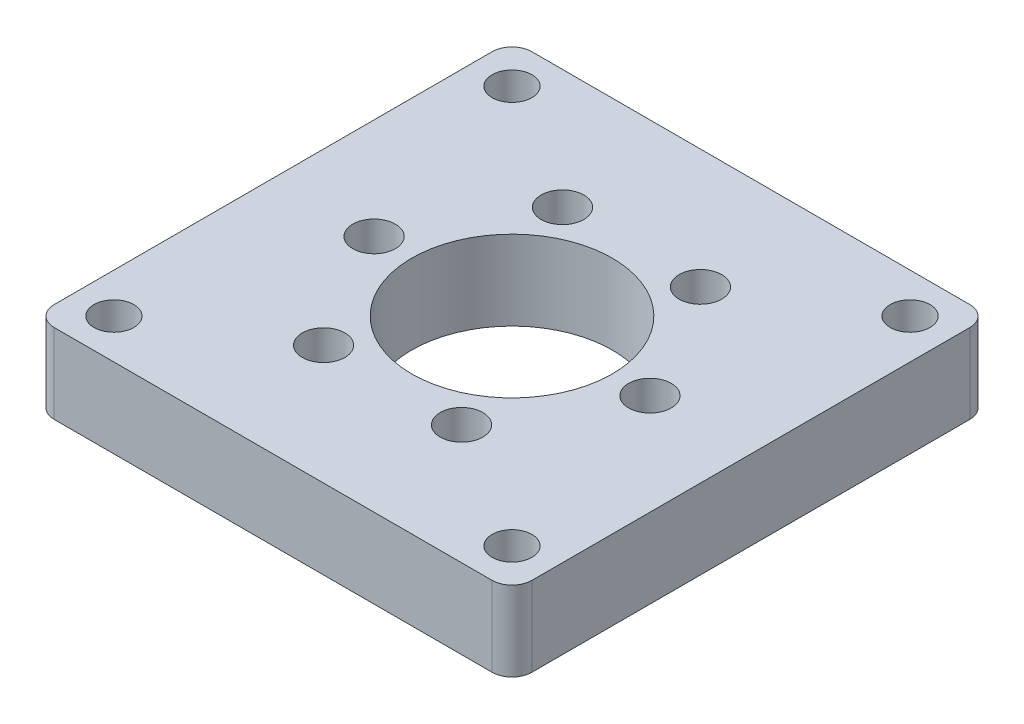
SolidWorks part; units mm, degrees
material "Balsa"
ref_plane "Front Plane" through (0, 0, 0) normal (0, 0, 1) x (1, 0, 0)
ref_plane "Top Plane" through (0, 0, 0) normal (0, 1, 0) x (1, 0, 0)
ref_plane "Right Plane" through (0, 0, 0) normal (1, 0, 0) x (0, 0, -1)
sketch "Sketch1" plane through (0, 0, 0) normal (0, 1, 0) x (1, 0, 0)
  line L1 (0, 0) -> (-38.1, 0)
  line L2 (0, 0) -> (0, -38.1)
  line L3 (0, -38.1) -> (-38.1, -38.1)
  line L4 (-38.1, 0) -> (-38.1, -38.1)
  dimension "D1" = 38.1
  dimension "D2" = 38.1
extrude "Boss-Extrude1" add sketch "Sketch1" along normal blind 6.35
sketch "Sketch5" plane through (0, 6.35, 0) normal (0, 1, 0) x (1, 0, 0)
  line L0 (-38.1, -19.05) -> (0, -19.05) construction
  line L1 (-38.1, 0) -> (-38.1, -38.1) construction
  line L2 (0, -38.1) -> (0, 0) construction
  circle A0 centre (-19.05, -19.05) radius 8
  dimension "D1" = 16
extrude "Cut-Extrude1" cut sketch "Sketch5" against normal through all
hole_wizard "M3 Clearance Hole1" positions "Sketch4" profile "Sketch3" hole size "M3" standard "Ansi Metric" end condition through all
sketch "Sketch4" plane through (0, 6.35, 0) normal (0, 1, 0) x (-1, 0, 0)
  line L0 (38.1, 19.05) -> (0, 19.05) construction
  line L1 (38.1, 0) -> (38.1, 38.1) construction
  line L2 (0, 38.1) -> (0, 0) construction
  line L4 (19.05, 19.05) -> (19.05, 38.1) construction
  line L5 (38.1, 38.1) -> (0, 38.1) construction
  line L7 (24.5504, 9.5231) -> (19.05, 19.05) construction
  line L9 (19.05, 19.05) -> (13.5496, 9.5231) construction
  line L10 (19.05, 19.05) -> (13.5496, 28.5769) construction
  line L12 (19.05, 19.05) -> (24.5504, 28.5769) construction
  line L14 (24.5504, 28.5769) -> (30.0507, 19.05) construction
  line L15 (30.0507, 19.05) -> (24.5504, 9.5231) construction
  line L16 (24.5504, 9.5231) -> (13.5496, 9.5231) construction
  line L17 (13.5496, 9.5231) -> (8.0493, 19.05) construction
  line L18 (8.0493, 19.05) -> (13.5496, 28.5769) construction
  line L19 (13.5496, 28.5769) -> (24.5504, 28.5769) construction
  circle A0 centre (19.05, 19.05) radius 11.0007 construction
  point P0 (30.0507, 19.05)
  point P24 (24.5504, 9.5231)
  point P25 (13.5496, 9.5231)
  point P26 (8.0493, 19.05)
  point P27 (13.5496, 28.5769)
  point P28 (24.5504, 28.5769)
  dimension "D1" = 11.0007
  dimension "D2" = 60
sketch "Sketch3" plane through (-30.0507, 6.35, 19.05) normal (1, 0, 0) x (0, 0, 1)
  line L0 (0, 0) -> (0, 6.35)
  line L1 (0, 6.35) -> (1.7, 6.35)
  line L2 (1.7, 6.35) -> (1.7, 0)
  line L5 (1.7, 0) -> (0, 0)
  line L11 (0, -6.35) -> (0, 107.95) construction
  dimension "Thru Hole Dia." = 3.4
  dimension "Thru Hole Depth" = 6.35
sketch "Sketch6" plane through (0, 6.35, 0) normal (0, 1, 0) x (1, 0, 0)
  line L0 (-19.05, 0) -> (-19.05, -38.1) construction
  line L1 (0, 0) -> (-38.1, 0) construction
  line L2 (-38.1, -38.1) -> (0, -38.1) construction
  line L3 (-19.05, -19.05) -> (-38.1, -19.05) construction
  line L4 (-38.1, 0) -> (-38.1, -38.1) construction
  line L5 (-34.925, -3.175) -> (-19.05, -3.175) construction
  line L6 (-34.925, -3.175) -> (-34.925, -19.05) construction
  circle A0 centre (-34.925, -3.175) radius 1.5875
  circle A1 centre (-3.175, -3.175) radius 1.5875
  circle A2 centre (-3.175, -34.925) radius 1.5875
  circle A3 centre (-34.925, -34.925) radius 1.5875
  dimension "D1" = 3.175
  dimension "D2" = 3.175
extrude "Cut-Extrude2" cut sketch "Sketch6" against normal through all
fillet "Fillet1" radius 1.5875 4 edges at (0, 3.175, 38.1) (-38.1, 3.175, 38.1) (0, 3.175, 0) (-38.1, 3.175, 0)
